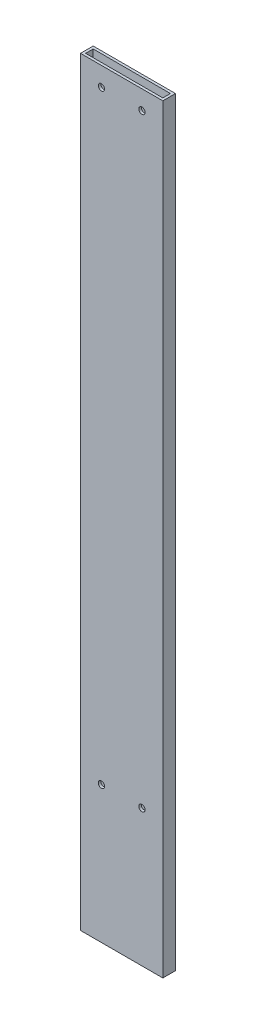
SolidWorks part; units mm, degrees
ref_plane "Front Plane" through (0, 0, 0) normal (0, 0, 1) x (1, 0, 0)
ref_plane "Top Plane" through (0, 0, 0) normal (0, 1, 0) x (1, 0, 0)
ref_plane "Right Plane" through (0, 0, 0) normal (1, 0, 0) x (0, 0, -1)
sketch "Sketch1" plane through (0, 0, 0) normal (0, 1, 0) x (1, 0, 0)
  line L0 (-30.5, 3) -> (30.5, 3)
  line L1 (-32.5, -5) -> (32.5, -5)
  line L2 (-32.5, -5) -> (-32.5, 5)
  line L3 (-32.5, 5) -> (32.5, 5)
  line L4 (32.5, -5) -> (32.5, 5)
  line L5 (-32.5, -5) -> (32.5, 5) construction
  line L6 (-32.5, 5) -> (32.5, -5) construction
  line L7 (30.5, -3) -> (30.5, 3)
  line L8 (-30.5, -3) -> (30.5, -3)
  line L9 (-30.5, -3) -> (-30.5, 3)
  point P0 (0, 0)
  dimension "D1" = 10
  dimension "D2" = 65
  dimension "D3" = 2
extrude "Boss-Extrude1" add sketch "Sketch1" along normal blind 600
sketch "Sketch2" plane through (0, 0, 5) normal (0, 0, 1) x (1, 0, 0)
  line L0 (0, 0) -> (0, 600) construction
  line L1 (32.5, 600) -> (-32.5, 600) construction
  line L2 (16, 108) -> (-16, 108) construction
  line L3 (-32.5, 600) -> (32.5, 600) construction
  line L5 (16, 585) -> (-16, 585) construction
  circle A0 centre (-16, 108) radius 2.5
  circle A1 centre (16, 108) radius 2.5
  circle A6 centre (16, 585) radius 2.5
  circle A7 centre (-16, 585) radius 2.5
  point P8 (0, 108)
  point P13 (0, 300)
  dimension "D1" = 5
  dimension "D2" = 32
  dimension "D3" = 108
  dimension "D4" = 15
extrude "Cut-Extrude1" cut sketch "Sketch2" against normal blind 600
